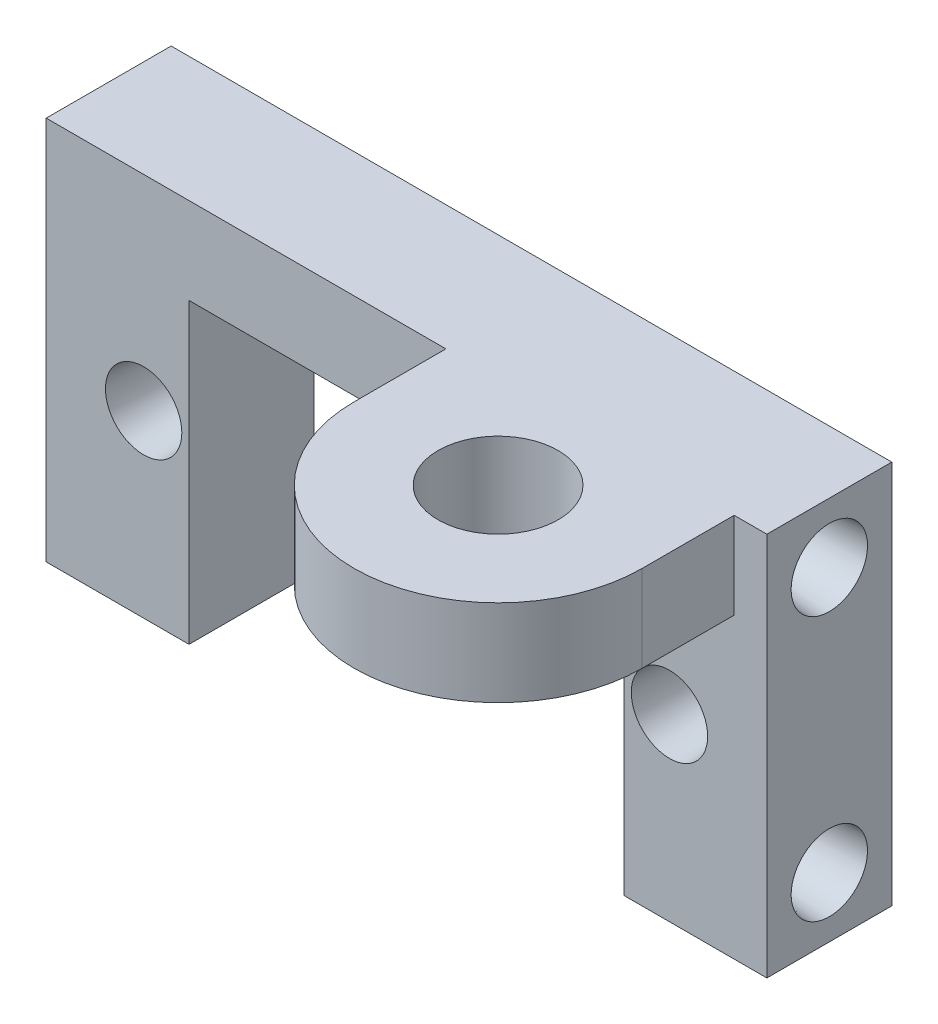
SolidWorks part; units mm, degrees
ref_plane "Front Plane" through (0, 0, 0) normal (0, 0, 1) x (1, 0, 0)
ref_plane "Top Plane" through (0, 0, 0) normal (0, 1, 0) x (1, 0, 0)
ref_plane "Right Plane" through (0, 0, 0) normal (1, 0, 0) x (0, 0, -1)
sketch "Sketch1" plane through (0, 0, 0) normal (0, 0, 1) x (1, 0, 0)
  line L0 (-11.5, -6.25) -> (-11.5, 6.25)
  line L1 (-11.5, 6.25) -> (11.5, 6.25)
  line L2 (11.5, 6.25) -> (11.5, -6.25)
  line L3 (11.5, -6.25) -> (19.05, -6.25) construction
  line L4 (19.05, -6.25) -> (19.05, 10.822)
  line L5 (19.05, 10.822) -> (-19.05, 10.822)
  line L6 (-19.05, 10.822) -> (-19.05, -6.25)
  line L7 (-19.05, -6.25) -> (-11.5, -6.25) construction
  line L8 (-11.5, 0) -> (0, 0) construction
  line L9 (0, 0) -> (0, 6.25) construction
  line L10 (-19.05, -6.25) -> (-19.05, -9.498)
  line L11 (-19.05, -9.498) -> (-11.5, -9.498)
  line L12 (-11.5, -9.498) -> (-11.5, -6.25)
  line L13 (11.5, -6.25) -> (11.5, -9.498)
  line L14 (11.5, -9.498) -> (19.05, -9.498)
  line L15 (19.05, -9.498) -> (19.05, -6.25)
  point P16 (11.5, -11.487)
  dimension "D1" = 23
  dimension "D2" = 12.5
  dimension "D3" = 4.572
  dimension "D4" = 38.1
  dimension "D5" = 20.32
extrude "Boss-Extrude1" add sketch "Sketch1" along normal blind 6.604
sketch "Sketch2" plane through (0, 10.822, 0) normal (0, 1, 0) x (1, 0, 0)
  line L0 (2.08, -11.464) -> (2.08, -6.604)
  line L1 (19.05, -6.604) -> (-19.05, -6.604) construction
  line L2 (2.08, -6.604) -> (17.32, -6.604)
  line L4 (17.32, -6.604) -> (17.32, -11.464)
  line L5 (0, 0) -> (0, -6.604) construction
  line L6 (19.05, 0) -> (-19.05, 0) construction
  circle A0 centre (9.7, -11.464) radius 3.175
  arc A1 (2.08, -11.464) -> (17.32, -11.464) centre (9.7, -11.464) ccw
  dimension "D1" = 6.35
  dimension "D2" = 4.86
  dimension "D3" = 7.62
  dimension "D4" = 9.7
extrude "Boss-Extrude2" add sketch "Sketch2" against normal up to surface (4.572 mm away) up to face at (0, 6.25, 3.302)
sketch "Sketch3" plane through (0, 0, 0) normal (0, 0, -1) x (-1, 0, 0)
  line L0 (-13.9, 0) -> (0, 0) construction
  line L1 (0, 0) -> (13.9, 0) construction
  circle A0 centre (13.9, 0) radius 1.7907
  circle A1 centre (-13.9, 0) radius 1.7907
  dimension "D1" = 3.5814
  dimension "D2" = 27.8
extrude "Cut-Extrude1" cut sketch "Sketch3" against normal through all
sketch "Sketch4" plane through (0, 0, 6.604) normal (0, 0, 1) x (1, 0, 0)
  circle A0 centre (-13.9, 0) radius 2.0193
  circle A1 centre (13.9, 0) radius 2.0193
  dimension "D1" = 4.0386
extrude "Cut-Extrude2" cut sketch "Sketch4" against normal through all draft 4
sketch "Sketch5" plane through (19.05, 0, 0) normal (1, 0, 0) x (0, 0, -1)
  line L0 (-3.302, 7.647) -> (-3.302, -6.323) construction
  line L1 (-6.604, 0.662) -> (-3.302, 0.662) construction
  line L2 (-6.604, -9.498) -> (-6.604, 10.822) construction
  line L3 (-3.302, 0.662) -> (0, 0.662) construction
  line L4 (0, -9.498) -> (0, 10.822) construction
  circle A0 centre (-3.302, 7.647) radius 1.7907
  circle A1 centre (-3.302, -6.323) radius 1.7907
  dimension "D1" = 3.5814
  dimension "D2" = 13.97
extrude "Cut-Extrude3" cut sketch "Sketch5" against normal blind 6.604
sketch "Sketch6" plane through (19.05, 0, 0) normal (1, 0, 0) x (0, 0, -1)
  circle A0 centre (-3.302, 7.647) radius 2.0193
  circle A1 centre (-3.302, -6.323) radius 2.0193
  dimension "D1" = 4.0386
extrude "Cut-Extrude4" cut sketch "Sketch6" against normal up to next (6.604 mm away) draft 4
